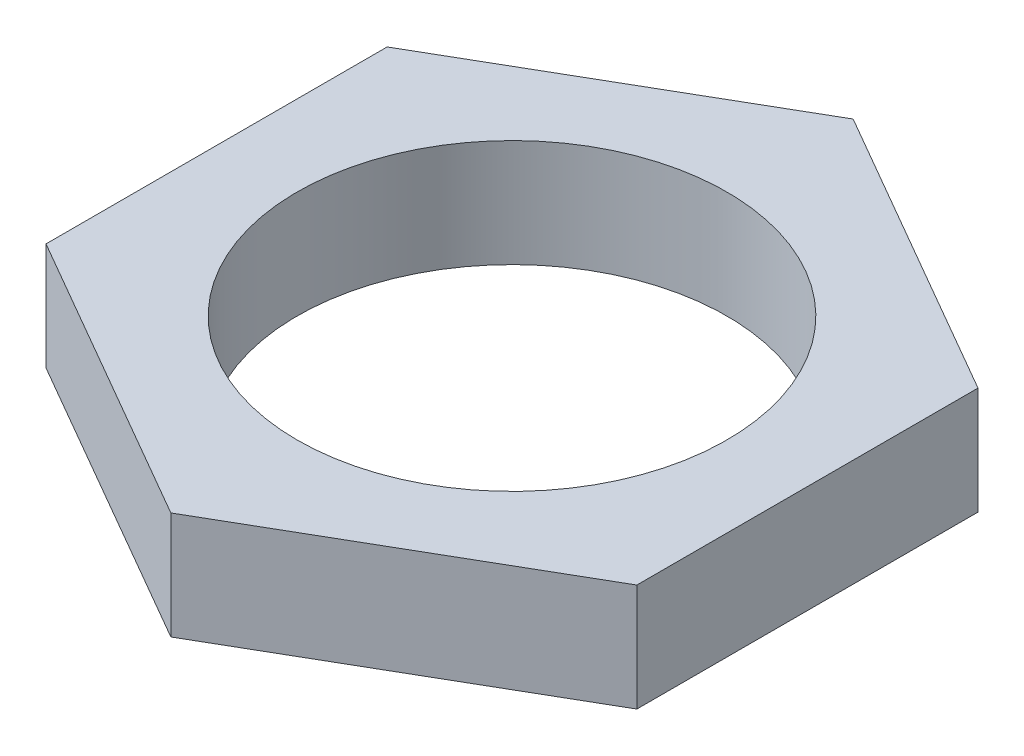
SolidWorks part; units mm, degrees
ref_plane "Спереди" through (0, 0, 0) normal (0, 0, 1) x (1, 0, 0)
ref_plane "Сверху" through (0, 0, 0) normal (0, 1, 0) x (1, 0, 0)
ref_plane "Справа" through (0, 0, 0) normal (1, 0, 0) x (0, 0, -1)
sketch "Эскиз1" plane through (0, 0, 0) normal (0, 1, 0) x (1, 0, 0)
  line L1 (0, 6.3509) -> (-5.5, 3.1754)
  line L2 (-5.5, 3.1754) -> (-5.5, -3.1754)
  line L3 (-5.5, -3.1754) -> (0, -6.3509)
  line L4 (0, -6.3509) -> (5.5, -3.1754)
  line L5 (5.5, -3.1754) -> (5.5, 3.1754)
  line L6 (5.5, 3.1754) -> (0, 6.3509)
  circle A0 centre (0, 0) radius 5.5 construction
  circle A1 centre (0, 0) radius 4
  dimension "D1" = 8
  dimension "D2" = 11
extrude "Бобышка-Вытянуть1" add sketch "Эскиз1" along normal blind 2
